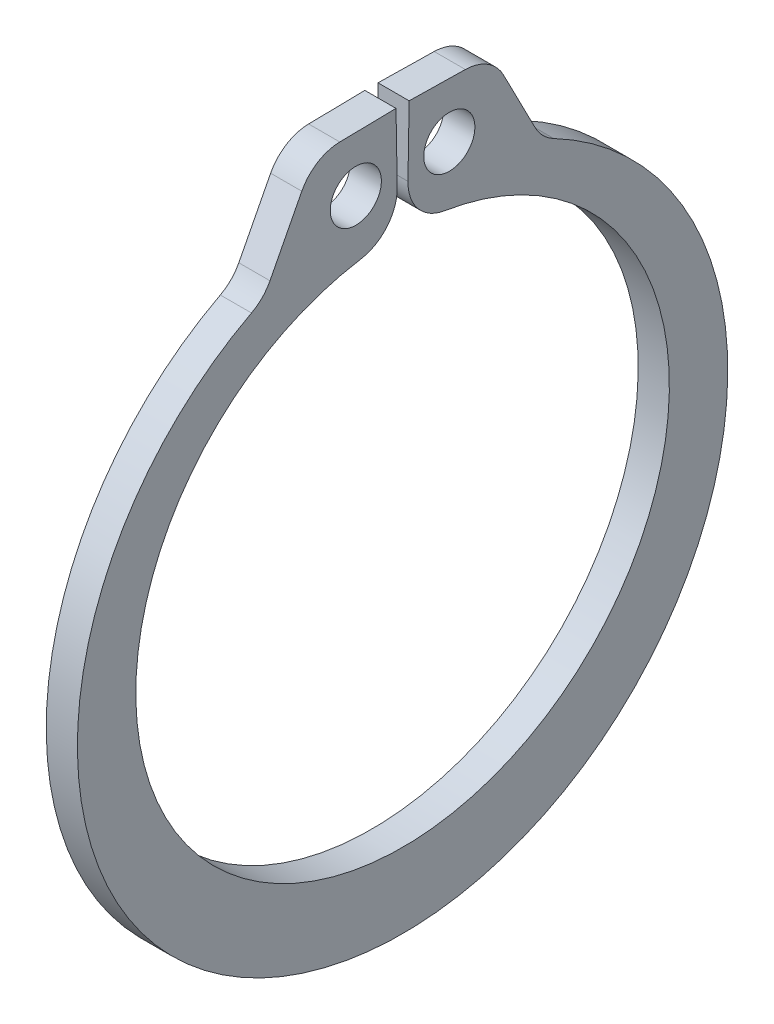
SolidWorks part; units mm, degrees
material "Cast Carbon Steel"
ref_plane "Front" through (0, 0, 0) normal (0, 0, 1) x (1, 0, 0)
ref_plane "Top" through (0, 0, 0) normal (0, 1, 0) x (1, 0, 0)
ref_plane "Right" through (0, 0, 0) normal (1, 0, 0) x (0, 0, -1)
sketch "Sketch1" plane through (0, 0, 0) normal (1, 0, 0) x (0, 0, -1)
  line L0 (0, 0) -> (0, 5.4356) construction
  line L1 (-0.0949, 5.4348) -> (-0.1339, 7.6696)
  line L2 (0.1339, 7.6696) -> (1.81, 7.6404)
  line L3 (1.81, 7.6404) -> (2.8346, 5.6538)
  line L4 (0.0949, 5.4348) -> (0.1339, 7.6696)
  line L5 (-0.1339, 7.6696) -> (-1.81, 7.6404)
  line L6 (-1.81, 7.6404) -> (-2.8346, 5.6538)
  line L7 (-2.8346, 5.6538) -> (-2.4361, 4.8591) construction
  line L8 (2.8346, 5.6538) -> (2.4361, 4.8591) construction
  line L9 (0, -5.4356) -> (0, -6.9596) construction
  line L10 (-1.81, 7.6404) -> (-0.0949, 5.4348) construction
  line L11 (0, 5.4356) -> (0, 7.6708) construction
  line L12 (-5.4356, 0) -> (5.4356, 0) construction
  circle A0 centre (0, 0) radius 5.4356 construction
  arc A1 (-0.0949, 5.4348) -> (0.0949, 5.4348) centre (0, 0) ccw
  circle A4 centre (-0.9524, 6.5376) radius 0.5207
  circle A5 centre (0.9524, 6.5376) radius 0.5207
  arc A6 (-2.8346, 5.6538) -> (2.8346, 5.6538) centre (0, -0.3344) ccw construction
  point P0 (0, -6.9596)
  dimension "Ring ID" = 10.8712
  dimension "Hole Diameter" = 1.0414
  dimension "Min. Sec." = 0.889
  dimension "Max. Sec." = 1.524
  dimension "Lug Height" = 2.2352
  dimension "D2" = 1.6764
  dimension "Angle" = 1
sketch "Sketch2" plane through (0, 0, 0) normal (0, 1, 0) x (1, 0, 0)
  line L0 (-0.3175, -6.6168) -> (0.3175, -6.6168) construction
  line L1 (0, -6.6252) -> (0, 6.6252) construction
  point P8 (0, -6.6168)
  dimension "Ring Thickness" = 0.635
sketch "Sketch3" plane through (0, 0, 0) normal (1, 0, 0) x (0, 0, -1)
  line L0 (-1.81, 7.6404) -> (-2.8346, 5.6538) construction
  line L1 (-1.81, 7.6404) -> (-2.8346, 5.6538)
  line L2 (-0.1339, 7.6696) -> (-1.81, 7.6404) construction
  line L3 (-0.1339, 7.6696) -> (-1.81, 7.6404)
  line L4 (-0.0949, 5.4348) -> (-0.1339, 7.6696) construction
  line L5 (-0.0949, 5.4348) -> (-0.1339, 7.6696)
  line L6 (0.0949, 5.4348) -> (0.1339, 7.6696) construction
  line L7 (0.0949, 5.4348) -> (0.1339, 7.6696)
  line L8 (0.1339, 7.6696) -> (1.81, 7.6404) construction
  line L9 (0.1339, 7.6696) -> (1.81, 7.6404)
  line L10 (1.81, 7.6404) -> (2.8346, 5.6538) construction
  line L11 (1.81, 7.6404) -> (2.8346, 5.6538)
  arc A0 (-2.8346, 5.6538) -> (2.8346, 5.6538) centre (0, -0.3344) ccw construction
  arc A1 (-2.8346, 5.6538) -> (2.8346, 5.6538) centre (0, -0.3344) ccw
  arc A2 (-0.0949, 5.4348) -> (0.0949, 5.4348) centre (0, 0) ccw construction
  arc A3 (-0.0949, 5.4348) -> (0.0949, 5.4348) centre (0, 0) ccw
  circle A4 centre (-0.9524, 6.5376) radius 0.5207 construction
  circle A5 centre (-0.9524, 6.5376) radius 0.5207
  circle A6 centre (0.9524, 6.5376) radius 0.5207 construction
  circle A7 centre (0.9524, 6.5376) radius 0.5207
extrude "Boss-Extrude1" add sketch "Sketch3" along normal up to vertex (0.3175 mm away) and the other way up to vertex (0.3175 mm away) up to point (0.3175, 0, 6.6168) other way up to point (-0.3175, 0, 6.6168)
fillet "Fillet1" radius 0.889 6 edges at (0, 5.6538, -2.8346) (0, 7.6404, -1.81) (0, 5.4348, -0.0949) (0, 5.4348, 0.0949) (0, 7.6404, 1.81) (0, 5.6538, 2.8346)
sketch "Sketch4" plane through (0, 0, 0) normal (1, 0, 0) x (0, 0, -1)
  line L0 (-4.7074, 2.7178) -> (0, 0) construction
  line L1 (0, 0) -> (0, 5.4356) construction
  line L2 (0, 7.6708) -> (0, 5.4356) construction
  arc A0 (-0.0949, 5.4348) -> (0.0949, 5.4348) centre (0, 0) ccw construction
  point P0 (0, 0)
  point P1 (-4.7074, 2.7178)
  dimension "D1" = 60
equation "\"D2@Sketch1\" = \"Lug Height@Sketch1\" * .75"
